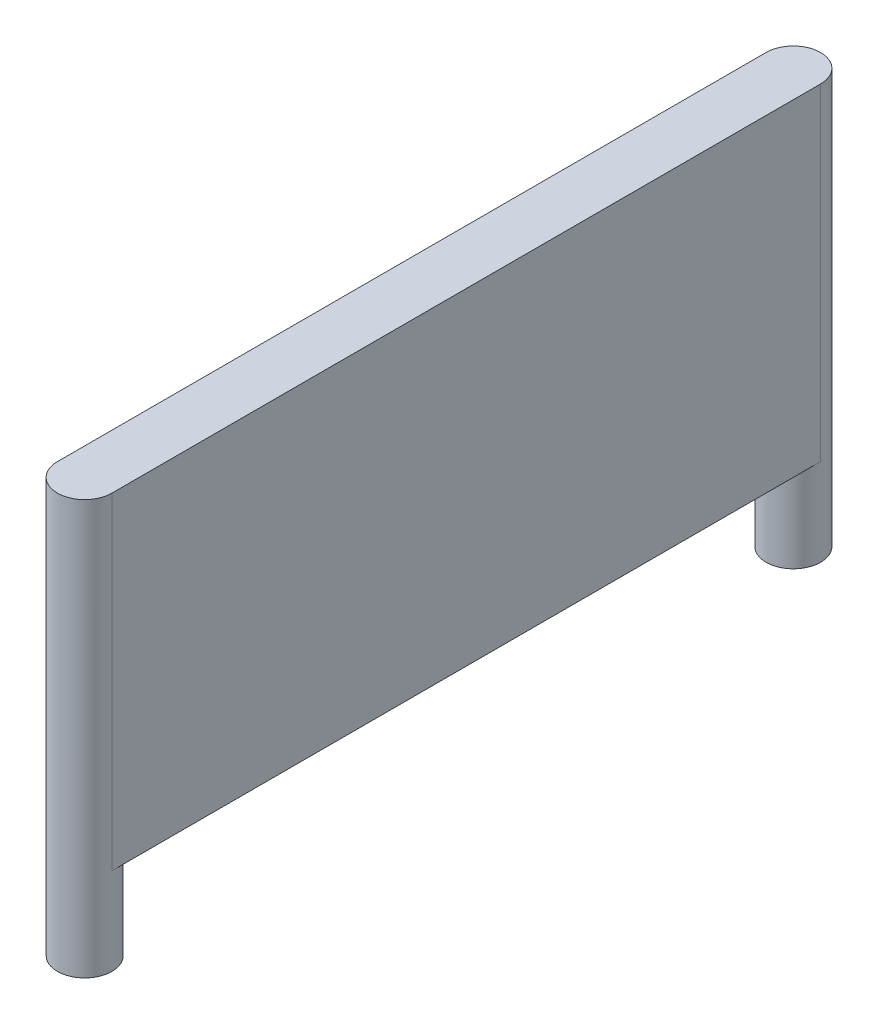
SolidWorks part; units mm, degrees
ref_plane "Front Plane" through (0, 0, 0) normal (0, 0, 1) x (1, 0, 0)
ref_plane "Top Plane" through (0, 0, 0) normal (0, 1, 0) x (1, 0, 0)
ref_plane "Right Plane" through (0, 0, 0) normal (1, 0, 0) x (0, 0, -1)
sketch "Sketch1" plane through (0, 0, 0) normal (0, 1, 0) x (1, 0, 0)
  line L0 (0, 0) -> (0, 82.55) construction
  line L1 (-3.175, 0) -> (-3.175, 82.55)
  line L2 (3.175, 0) -> (3.175, 82.55)
  arc A0 (-3.175, 0) -> (3.175, 0) centre (0, 0) ccw
  arc A1 (3.175, 82.55) -> (-3.175, 82.55) centre (0, 82.55) ccw
  point P3 (0, 41.275)
  dimension "D1" = 6.35
  dimension "D2" = 82.55
extrude "Boss-Extrude1" add sketch "Sketch1" along normal blind 38.1
sketch "Sketch2" plane through (0, 0, 0) normal (0, -1, 0) x (-1, 0, 0)
  circle A0 centre (0, 82.55) radius 3.175
  circle A1 centre (0, 0) radius 3.175
extrude "Boss-Extrude2" add sketch "Sketch2" along normal blind 10.16
